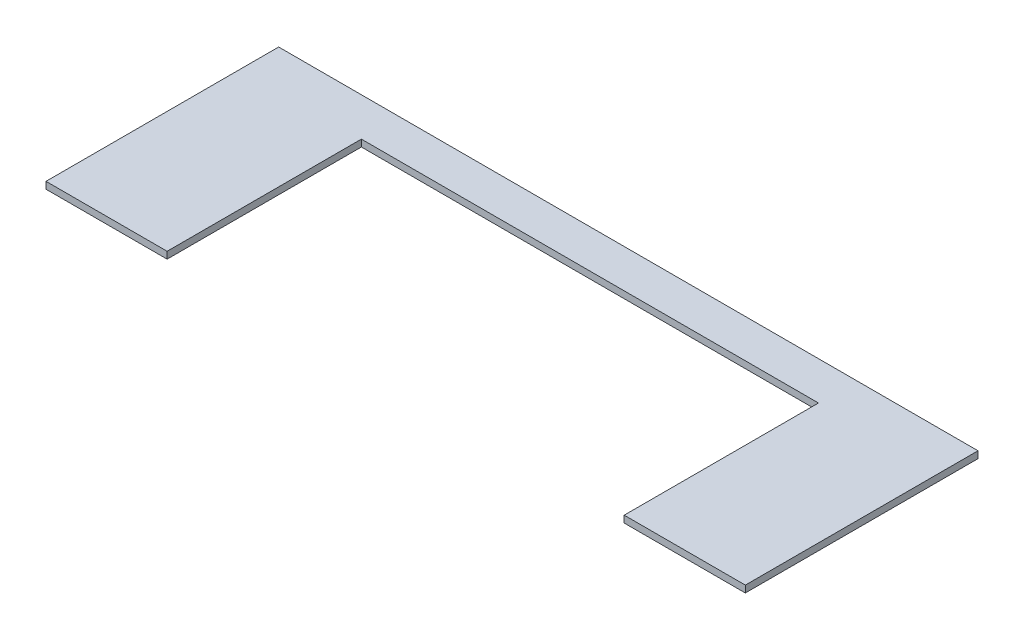
SolidWorks part; units mm, degrees
ref_plane "Front" through (0, 0, 0) normal (0, 0, 1) x (1, 0, 0)
ref_plane "Top" through (0, 0, 0) normal (0, 1, 0) x (1, 0, 0)
ref_plane "Right" through (0, 0, 0) normal (1, 0, 0) x (0, 0, -1)
sketch "Эскиз1" plane through (0, 0, 0) normal (0, 1, 0) x (1, 0, 0)
  line L1 (1967.0612, 2074.5043) -> (2579.0612, 2074.5043)
  line L2 (1967.0612, 2074.5043) -> (1967.0612, 1870.8971)
  line L3 (1967.0612, 1870.8971) -> (2579.0612, 1870.8971)
  line L4 (2579.0612, 2074.5043) -> (2579.0612, 1870.8971)
extrude "Бобышка-Вытянуть1" add sketch "Эскиз1" along normal blind 6
sketch "Эскиз2" plane through (0, 6, 0) normal (0, 1, 0) x (1, 0, 0)
  line L0 (1967.0612, 1870.8971) -> (2579.0612, 1870.8971) construction
  line L1 (2073.0612, 1870.8971) -> (2473.0612, 1870.8971)
  line L2 (2073.0612, 1870.8971) -> (2073.0612, 2040.8971)
  line L3 (2073.0612, 2040.8971) -> (2473.0612, 2040.8971)
  line L4 (2473.0612, 1870.8971) -> (2473.0612, 2040.8971)
  line L5 (2273.0612, 2074.5043) -> (2273.0612, -164.5111) construction
  line L6 (2579.0612, 2074.5043) -> (1967.0612, 2074.5043) construction
  point P10 (2273.0612, 2040.8971)
  dimension "D1" = 170
  dimension "D2" = 400
extrude "Вырез-Вытянуть1" cut sketch "Эскиз2" against normal up to surface (6 mm away) up to face at (2273.0612, 0, -1972.7007)
